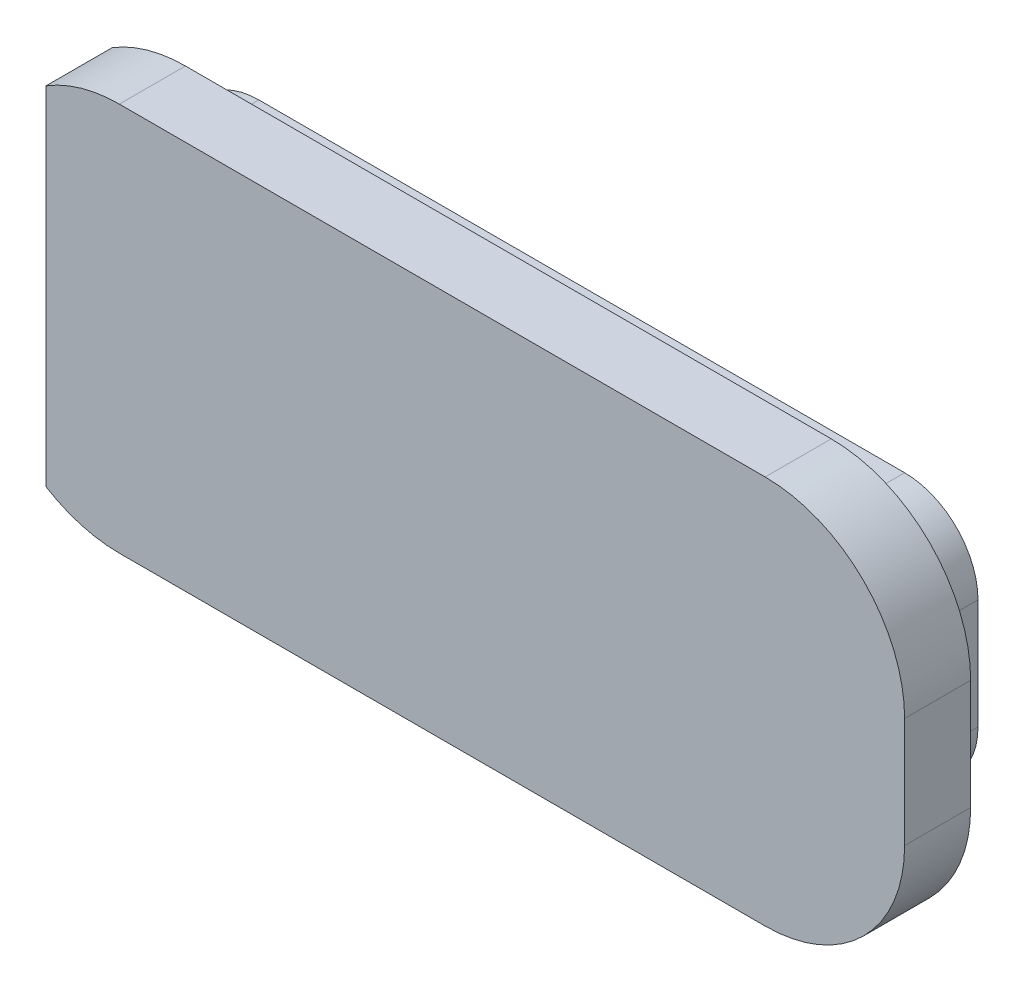
SolidWorks part; units mm, degrees
ref_plane "Front Plane" through (0, 0, 0) normal (0, 0, 1) x (1, 0, 0)
ref_plane "Top Plane" through (0, 0, 0) normal (0, 1, 0) x (1, 0, 0)
ref_plane "Right Plane" through (0, 0, 0) normal (1, 0, 0) x (0, 0, -1)
sketch "Locating_tongue_profile" plane through (0, 0, 0) normal (0, 0, 1) x (1, 0, 0)
  line L0 (1, 0) -> (9.8, 0)
  line L1 (10.8, 1) -> (10.8, 2.5)
  line L2 (9.8, 3.5) -> (1, 3.5)
  line L3 (0, 2.5) -> (0, 1)
  arc A0 (9.8, 0) -> (10.8, 1) centre (9.8, 1) ccw
  arc A1 (10.8, 2.5) -> (9.8, 3.5) centre (9.8, 2.5) ccw
  arc A2 (1, 3.5) -> (0, 2.5) centre (1, 2.5) ccw
  arc A3 (0, 1) -> (1, 0) centre (1, 1) ccw
extrude "Locating_tongue" add sketch "Locating_tongue_profile" against normal blind 1
sketch "Cover_flange_profile" plane through (0, 0, 0) normal (0, 0, 1) x (1, 0, 0)
  line L0 (0, -0.6155) -> (0, 4.1155)
  line L1 (1, 4.4) -> (9.8, 4.4)
  line L2 (11.7, 2.5) -> (11.7, 1)
  line L3 (9.8, -0.9) -> (1, -0.9)
  arc A0 (1, 4.4) -> (0, 4.1155) centre (1, 2.5) ccw
  arc A1 (11.7, 2.5) -> (9.8, 4.4) centre (9.8, 2.5) ccw
  arc A2 (9.8, -0.9) -> (11.7, 1) centre (9.8, 1) ccw
  arc A3 (0, -0.6155) -> (1, -0.9) centre (1, 1) ccw
extrude "Cover_flange" add sketch "Cover_flange_profile" along normal blind 0.9
